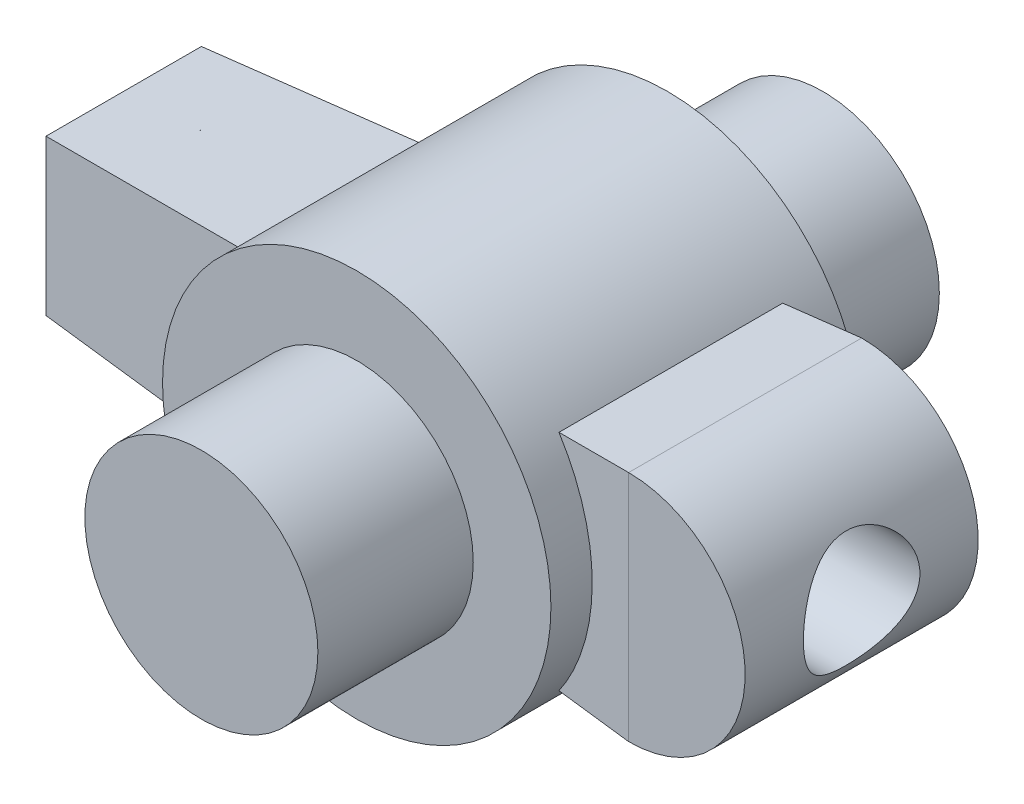
SolidWorks part; units mm, degrees
ref_plane "Front Plane" through (0, 0, 0) normal (0, 0, 1) x (1, 0, 0)
ref_plane "Top Plane" through (0, 0, 0) normal (0, 1, 0) x (1, 0, 0)
ref_plane "Right Plane" through (0, 0, 0) normal (1, 0, 0) x (0, 0, -1)
sketch "Sketch1" plane through (0, 0, 0) normal (1, 0, 0) x (0, 0, -1)
  line L0 (-74.698, 0) -> (76.9128, 0) construction
  line L1 (0, 0) -> (-40, 0)
  line L2 (-40, 0) -> (-40, 15)
  line L3 (-40, 15) -> (-20, 15)
  line L4 (-20, 15) -> (-20, 25)
  line L5 (-20, 25) -> (20, 25)
  line L6 (20, 25) -> (20, 15)
  line L7 (20, 15) -> (40, 15)
  line L8 (40, 15) -> (40, 0)
  line L9 (40, 0) -> (0, 0)
  point P13 (0, 25)
  dimension "D1" = 15
  dimension "D2" = 10
  dimension "D3" = 20
  dimension "D4" = 40
revolve "Revolve1" add sketch "Sketch1" angle 360 about L0
ref_plane "Plane1" through (30, 0, 0) normal (1, 0, 0) x (0, 0, -1)
ref_plane "Plane2" through (-50, 0, 0) normal (1, 0, 0) x (0, 0, -1)
sketch "Sketch3" plane through (-50, 0, 0) normal (1, 0, 0) x (0, 0, -1)
  line L1 (-10, 10) -> (10, 10)
  line L2 (-10, 10) -> (-10, -10)
  line L3 (-10, -10) -> (10, -10)
  line L4 (10, 10) -> (10, -10)
  line L5 (-10, 10) -> (10, -10) construction
  line L6 (-10, -10) -> (10, 10) construction
  point P0 (0, 0)
  dimension "D1" = 20
  dimension "D2" = 20
sketch "Sketch4" plane through (30, 0, 0) normal (1, 0, 0) x (0, 0, -1)
  line L1 (-15, 15) -> (15, 15)
  line L2 (-15, 15) -> (-15, -15)
  line L3 (-15, -15) -> (15, -15)
  line L4 (15, 15) -> (15, -15)
  line L5 (-15, 15) -> (15, -15) construction
  line L6 (-15, -15) -> (15, 15) construction
  point P0 (0, 0)
  dimension "D1" = 30
  dimension "D2" = 30
loft "Loft1" add profiles "Sketch3", "Sketch4"
sketch "Sketch7" plane through (0, 0, 0) normal (0, 0, 1) x (1, 0, 0)
  line L0 (30, 15) -> (30, -15) construction
  line L1 (30, 15) -> (30, -15)
  arc A0 (30, 15) -> (30, -15) centre (30, 0) cw
extrude "Boss-Extrude1" add sketch "Sketch7" along normal mid plane 30
sketch "Sketch8" plane through (-50, 0, 0) normal (-1, 0, 0) x (0, 0, 1)
  circle A0 centre (0, 0) radius 7.5
  dimension "D1" = 15
extrude "Cut-Extrude1" cut sketch "Sketch8" against normal through all both and the other way through all
sketch "Sketch9" plane through (0, 0, -40) normal (0, 0, -1) x (-1, 0, 0)
  line L0 (0, 0) -> (0, 29.3703) construction
  line L1 (0, 0) -> (0, 7.2) construction
  circle A0 centre (0, 0) radius 16 construction
  circle A1 centre (0, 0) radius 13.6 construction
  circle A2 centre (0, 0) radius 10.4 construction
  circle A3 centre (0, 0) radius 7.2 construction
  circle A4 centre (0, 7.2) radius 0.75
  circle A5 centre (0, 10.4) radius 0.75
  circle A6 centre (0, 13.6) radius 0.75
  circle A7 centre (11.7779, 6.8) radius 0.75
  circle A8 centre (9.0067, 5.2) radius 0.75
  circle A9 centre (6.2354, 3.6) radius 0.75
  circle A10 centre (11.7779, -6.8) radius 0.75
  circle A11 centre (9.0067, -5.2) radius 0.75
  circle A12 centre (6.2354, -3.6) radius 0.75
  circle A13 centre (0, -13.6) radius 0.75
  circle A14 centre (0, -10.4) radius 0.75
  circle A15 centre (0, -7.2) radius 0.75
  circle A16 centre (-11.7779, -6.8) radius 0.75
  circle A17 centre (-9.0067, -5.2) radius 0.75
  circle A18 centre (-6.2354, -3.6) radius 0.75
  circle A19 centre (-11.7779, 6.8) radius 0.75
  circle A20 centre (-9.0067, 5.2) radius 0.75
  circle A21 centre (-6.2354, 3.6) radius 0.75
  circle A22 centre (0, 0) radius 3
  dimension "D1" = 32
  dimension "D2" = 27.2
  dimension "D3" = 20.8
  dimension "D4" = 14.4
  dimension "D5" = 1.5
  dimension "D6" = 1.5
  dimension "D7" = 1.5
  dimension "D10" = 6
  dimension "D9" = 7.2
  dimension "D8" = 6
extrude "Cut-Extrude2" cut sketch "Sketch9" against normal blind 8 and the other way through all
